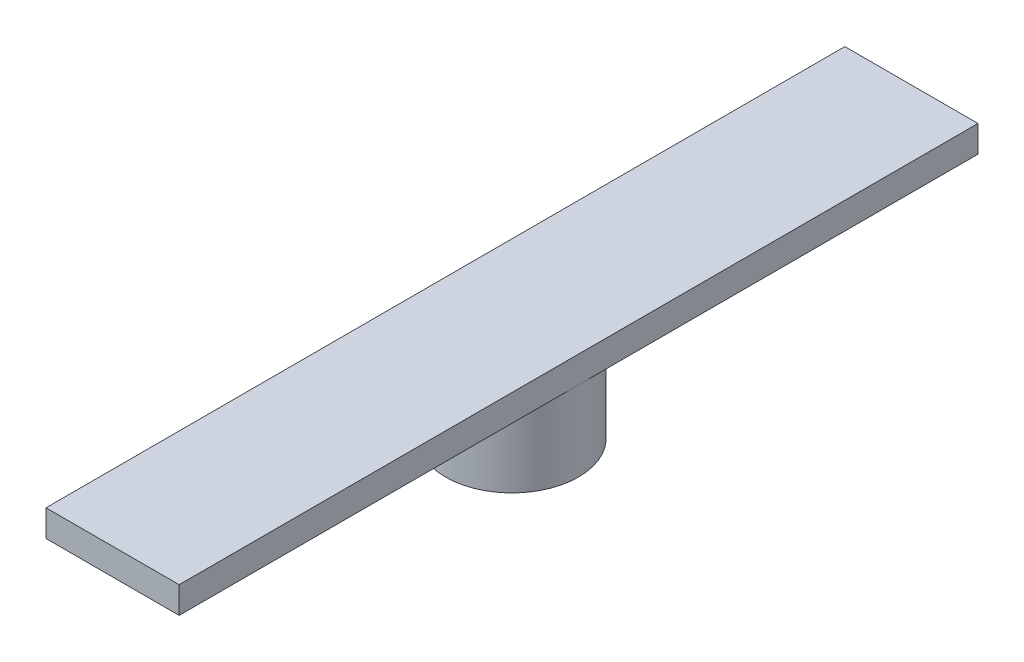
SolidWorks part; units mm, degrees
ref_plane "Plan de face" through (0, 0, 0) normal (0, 0, 1) x (1, 0, 0)
ref_plane "Plan de dessus" through (0, 0, 0) normal (0, 1, 0) x (1, 0, 0)
ref_plane "Plan de droite" through (0, 0, 0) normal (1, 0, 0) x (0, 0, -1)
sketch "Esquisse1" plane through (0, 0, 0) normal (0, 1, 0) x (1, 0, 0)
  circle A0 centre (0, 0) radius 2.5
  dimension "D1" = 5
extrude "Boss.-Extru.1" add sketch "Esquisse1" along normal blind 3
sketch "Esquisse2" plane through (0, 3, 0) normal (0, 1, 0) x (1, 0, 0)
  line L1 (-2.5, -15) -> (2.5, -15)
  line L2 (-2.5, -15) -> (-2.5, 15)
  line L3 (-2.5, 15) -> (2.5, 15)
  line L4 (2.5, -15) -> (2.5, 15)
  line L5 (-2.5, -15) -> (2.5, 15) construction
  line L6 (-2.5, 15) -> (2.5, -15) construction
  point P0 (0, 0)
  dimension "D1" = 5
  dimension "D2" = 30
extrude "Boss.-Extru.2" add sketch "Esquisse2" along normal blind 1
